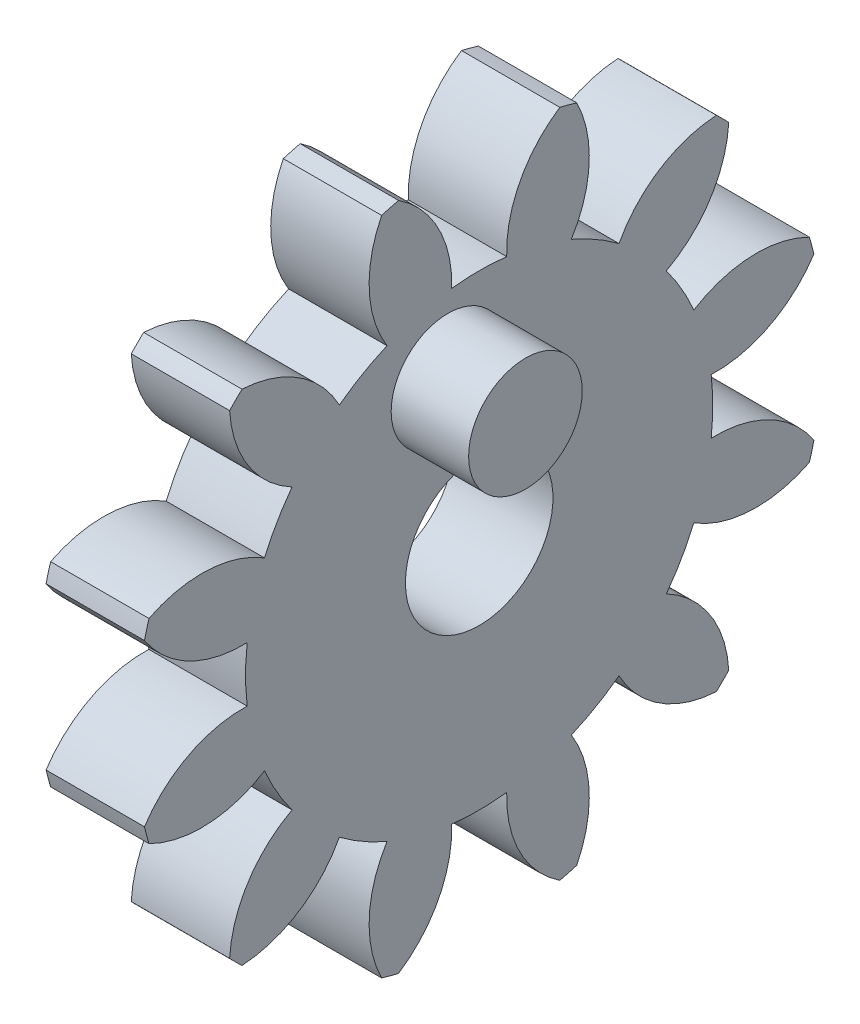
SolidWorks part; units mm, degrees
ref_plane "Plane1" through (0, 0, 0) normal (0, 0, 1) x (1, 0, 0)
ref_plane "Plane2" through (0, 0, 0) normal (0, 1, 0) x (1, 0, 0)
ref_plane "Plane3" through (0, 0, 0) normal (1, 0, 0) x (0, 0, -1)
other "Configuration Table"
sketch "HoldingSke" plane through (0, 0, 0) normal (0, 1, 0) x (1, 0, 0)
  line L0 (0, 0) -> (0.1551, -0.0273)
  line L1 (-15, 0) -> (100, 0) construction
  line L2 (0, 0) -> (-2.1039, 2.3779)
  line L3 (0, 0) -> (-11.863, 4.5341)
  line L4 (0, 0) -> (8.5048, 1.4996)
  line L5 (0, 0) -> (-46.8476, -17.4728)
  line L6 (0, 0) -> (-10.5278, -7.1032)
  line L7 (-2.1039, 2.3779) -> (3.3635, 27.1825)
  line L8 (-76.2, 54.61) -> (-76.1, 54.61)
  line L9 (-71.009, 38.7566) -> (-53.1078, 45.2721)
  line L10 (-76.2, 71.12) -> (104.1128, 71.12)
  line L11 (0, 0) -> (-12, 0)
  line L12 (-76.2, 101.6) -> (-76.192, 101.6)
  line L13 (24.9733, 27.94) -> (52.9518, 28.4284)
  line L14 (24.9733, 27.94) -> (24.9743, 27.94)
  line L15 (24.9733, 27.94) -> (100.4006, 29.5858)
  line L16 (-63.627, -0.25) -> (-12.827, -0.25)
  circle A0 centre (0, 0) radius 0.4
  circle A1 centre (0, 0) radius 12.7
  circle A2 centre (0, 0) radius 37.5
  circle A3 centre (0, 0) radius 9.525
  dimension "MHD" = 25.4
  dimension "Hub_dia" = 75
  dimension "Bore" = 0.8
  dimension "MBD" = 19.05
  dimension "Num_teeth" = 10
  dimension "Pitch" = 0.1575
  dimension "Overall_len" = 50
  dimension "Show_teeth" = 10
  dimension "Thickness" = 12.7
  dimension "OAL" = 25.4001
  dimension "T_dim" = 0.1
  dimension "Ap" = 20
  dimension "H" = 19.05
  dimension "Pitch_radius" = 180.3128
  dimension "Width" = 12
  dimension "Backlash" = 0.008
  dimension "Addendum_fac" = 1
  dimension "Dedendum_fac" = 1.25
  dimension "Clearance_fac" = 0.25
  dimension "Dedendum_add" = 0.001
  dimension "Module" = 0.25
sketch "BasProSke" plane through (0, 0, 0) normal (0, 1, 0) x (1, 0, 0)
  line L0 (-10, 0) -> (60, 0) construction
  line L1 (0, 0) -> (0, 44.45)
  line L2 (0, 0) -> (12.7, 0)
  line L3 (12.7, 0) -> (12.7, 44.45)
  line L4 (12.7, 44.45) -> (0, 44.45)
  dimension "Thickness" = 12.7
  dimension "Diameter" = 88.9
revolve "Base-Revolve" add sketch "BasProSke" angle 360 about L0
sketch "TooCutSke" plane through (0, 0, 0) normal (1, 0, 0) x (0, 0, -1)
  line L1 (0, 0) -> (0, 107) construction
  line L2 (0, 0) -> (-5.3725, 37.7193) construction
  line L3 (0, 0) -> (-19.5794, 73.0714) construction
  line L4 (-5.3725, 37.7193) -> (-9.7897, 36.5357) construction
  arc A0 (3.5522, 29.9513) -> (-3.5522, 29.9513) centre (0, 0) ccw
  arc A1 (10.4397, 43.2328) -> (-10.4397, 43.2328) centre (0, 0) ccw
  circle A2 centre (0, 0) radius 38.1 construction
  circle A3 centre (0, 0) radius 35.8023 construction
  arc A4 (-3.5522, 29.9513) -> (-10.4397, 43.2328) centre (-18.7831, 30.4795) ccw
  arc A5 (10.4397, 43.2328) -> (3.5522, 29.9513) centre (18.7831, 30.4795) ccw
  dimension "Root_dia" = 60.3225
  dimension "Overcut_dia" = 88.9508
  dimension "Pitch_dia" = 76.2
  dimension "Base_dia" = 71.6046
  dimension "Flank_rad" = 15.24
  dimension "Half_ang" = 15
  dimension "Half_CT" = 4.573
extrude "ToothCut" cut sketch "TooCutSke" along normal through all
fillet "Breaks" [suppressed] radius 0.127
fillet "RootFillets" [suppressed] radius 1.5888
pattern_circular "TeethCuts" count 12 every 30 about axis through (-10, 0, 0) along (1, 0, 0) of "ToothCut", "RootFillets", "Breaks"
sketch "HubNeaOneSke" plane through (0, 0, 0) normal (-1, 0, 0) x (0, 0, 1)
  circle A0 centre (0, 0) radius 12.7
  dimension "Diameter" = 25.4
extrude "HubNearOne" [suppressed] add sketch "HubNeaOneSke" along normal blind 12.7001
sketch "HubNeaBotSke" plane through (0, 0, 0) normal (-1, 0, 0) x (0, 0, 1)
  circle A0 centre (0, 0) radius 12.7
  dimension "Diameter" = 25.4
extrude "HubNearBoth" [suppressed] add sketch "HubNeaBotSke" along normal blind 6.35
ref_plane "FarPln" through (12.7, 0, 0) normal (1, 0, 0) x (0, 0, -1)
sketch "HubFarSke" plane through (12.7, 0, 0) normal (1, 0, 0) x (0, 0, -1)
  circle A0 centre (0, 0) radius 12.7
  dimension "Diameter" = 25.4
extrude "HubFar" [suppressed] add sketch "HubFarSke" along normal blind 6.35
sketch "BorSke" plane through (0, 0, 0) normal (1, 0, 0) x (0, 0, -1)
  circle A0 centre (0, 0) radius 9.525
  dimension "Diameter" = 19.05
extrude "Bore" cut sketch "BorSke" along normal mid plane 50.8001
sketch "KeySke" plane through (0, 0, 0) normal (1, 0, 0) x (0, 0, -1)
  line L0 (-0.05, 0) -> (-0.05, 12.065)
  line L1 (-0.05, 12.065) -> (0.05, 12.065)
  line L2 (0.05, 12.065) -> (0.05, 0)
  line L3 (0, 0) -> (0, 34) construction
  line L4 (-0.05, 0) -> (0.05, 0)
  dimension "Offset" = 12.065
  dimension "Width" = 0.1
extrude "Keyway" [suppressed] cut sketch "KeySke" along normal mid plane 50.8001
pattern_circular "Keyway2" [suppressed] count 2 every 90 about axis through (-10, 0, 0) along (1, 0, 0)
sketch "Sketch1" plane through (12.7, 0, 0) normal (1, 0, 0) x (0, 0, -1)
  circle A0 centre (-4.0293, 20.066) radius 7.3334
extrude "Boss-Extrude1" add sketch "Sketch1" along normal blind 10
equation "' \"Module@HoldingSke\" = 6.35"
equation "' \"Num_teeth@HoldingSke\" = 12"
equation "' \"Ap@HoldingSke\" =  20"
equation "' \"Ap@HoldingSke\" = 20"
equation "' \"Width@HoldingSke\" = 0.5 * 25.4"
equation "' \"Hub_dia@HoldingSke\"= 1 * 25.4"
equation "' \"Hub_dia@HoldingSke\" = 1 * 25.4"
equation "' \"Overall_len@HoldingSke\" = 1.0 * 25.4"
equation "' \"Bore@HoldingSke\" = 0.75 * 25.4"
equation "' \"T_dim@HoldingSke\" = 0.1 * 25.4"
equation "' \"Width@KeySke\" = 0.25 * 25.4"
equation "' \"Show_teeth@HoldingSke\" = 13"
equation "' \"Backlash@HoldingSke\" = 0.009 * 25.4"
equation "' \"Addendum_fac@HoldingSke\" = 1.0"
equation "' \"Dedendum_fac@HoldingSke\" = 1.25"
equation "' \"Dedendum_add@HoldingSke\" = 0.00005 * 25.4"
equation "' \"Clearance_fac@HoldingSke\" = 0.25"
equation "\"Pitch@HoldingSke\" = 1 / \"Module@HoldingSke\""
equation "\"Overcut_dia@TooCutSke\" = (\"Num_teeth@HoldingSke\" + 2 * \"Addendum_fac@HoldingSke\") / \"Pitch@HoldingSke\" + 0.002 * 25.4"
equation "\"Pitch_dia@TooCutSke\" = \"Num_teeth@HoldingSke\" / \"Pitch@HoldingSke\""
equation "\"Base_dia@TooCutSke\" = \"Num_teeth@HoldingSke\" / \"Pitch@HoldingSke\" * cos((\"Ap@HoldingSke\"  * 3.14159265 / 180))"
equation "\"Root_dia@TooCutSke\" = (\"Num_teeth@HoldingSke\" + 2) / \"Pitch@HoldingSke\" - 2 * (\"Addendum_fac@HoldingSke\" + \"Dedendum_fac@HoldingSke\") / \"Pitch@HoldingSke\" - \"Dedendum_add@HoldingSke\" * 2"
equation "\"Half_ang@TooCutSke\" = 180 / \"Num_teeth@HoldingSke\""
equation "\"Half_CT@TooCutSke\" = \"Num_teeth@HoldingSke\" / \"Pitch@HoldingSke\" * sin((3.14159265 / 2 / \"Num_teeth@HoldingSke\")) / 2 - 7 * \"Backlash@HoldingSke\" / 4"
equation "\"Flank_rad@TooCutSke\" = \"Num_teeth@HoldingSke\" / \"Pitch@HoldingSke\" / 5"
equation "\"Radius@RootFillets\" = \"Clearance_fac@HoldingSke\" / \"Pitch@HoldingSke\" + \"Dedendum_add@HoldingSke\""
equation "\"Break_rad@Breaks\" = 0.02 / \"Pitch@HoldingSke\""
equation "\"Thickness@HoldingSke\" = \"Width@HoldingSke\""
equation "\"OAL@HoldingSke\" = \"Thickness@HoldingSke\""
equation "\"MHD@HoldingSke\" = (\"Num_teeth@HoldingSke\" + 2) / \"Pitch@HoldingSke\" - 2 * (\"Addendum_fac@HoldingSke\" + \"Dedendum_fac@HoldingSke\")  / \"Pitch@HoldingSke\" - \"Dedendum_add@HoldingSke\" * 2"
equation "\"MBD@HoldingSke\" = (\"Num_teeth@HoldingSke\" + 2) / \"Pitch@HoldingSke\" - 2 * (\"Addendum_fac@HoldingSke\" + \"Dedendum_fac@HoldingSke\")  / \"Pitch@HoldingSke\" - \"Dedendum_add@HoldingSke\" * 2 - 0.002 * 25.4"
equation "\"MHD@HoldingSke\" = ((sgn( \"MHD@HoldingSke\" - \"Hub_dia@HoldingSke\" )-1)*( \"MHD@HoldingSke\" - \"Hub_dia@HoldingSke\" ))/-2+ \"Hub_dia@HoldingSke\""
equation "\"MBD@HoldingSke\" = ((sgn( \"MBD@HoldingSke\" - \"Bore@HoldingSke\" )-1)*( \"MBD@HoldingSke\" - \"Bore@HoldingSke\" ))/-2+ \"Bore@HoldingSke\""
equation "\"OAL@HoldingSke\" = ((sgn( \"OAL@HoldingSke\" - \"Overall_len@HoldingSke\" )+1)*( \"OAL@HoldingSke\" - \"Overall_len@HoldingSke\" ))/2 + \"Overall_len@HoldingSke\" + 0.000002 * 25.4"
equation "\"Num_teeth@TeethCuts\" = int( \"Show_teeth@HoldingSke\" ) + 1"
equation "\"Num_teeth@TeethCuts\" = ((sgn( \"Num_teeth@TeethCuts\" - \"Num_teeth@HoldingSke\" )-1)*( \"Num_teeth@TeethCuts\" - \"Num_teeth@HoldingSke\" ))/-2+ \"Num_teeth@HoldingSke\""
equation "\"Num_teeth@TeethCuts\" = ((sgn( \"Num_teeth@TeethCuts\" - 2.0)+1)*( \"Num_teeth@TeethCuts\" - 2.0))/2 +2.0"
equation "\"Angle@TeethCuts\" = 360.0 / \"Num_teeth@HoldingSke\""
equation "\"Diameter@BasProSke\" = (\"Num_teeth@HoldingSke\" + 2 * \"Addendum_fac@HoldingSke\") / \"Pitch@HoldingSke\""
equation "\"Thickness@BasProSke\"  = \"Thickness@HoldingSke\""
equation "' \"Fillet_rad@BasProSke\" =  \"Thickness@HoldingSke\" * 0.05"
equation "' \"Fillet_rad@BasProSke\" = \"Thickness@HoldingSke\" * 0.05"
equation "\"MHD@HoldingSke\" = ((sgn( \"MHD@HoldingSke\" - \"Root_dia@TooCutSke\" )-1)*( \"MHD@HoldingSke\" - \"Root_dia@TooCutSke\" ))/-2+ \"Root_dia@TooCutSke\""
equation "\"Diameter@HubNeaOneSke\" = \"MHD@HoldingSke\""
equation "\"Length@HubNearOne\" = \"OAL@HoldingSke\" - \"Thickness@BasProSke\""
equation "\"Diameter@HubNeaBotSke\" = \"MHD@HoldingSke\""
equation "\"Length@HubNearBoth\" = ( \"OAL@HoldingSke\" - \"Thickness@BasProSke\" ) / 2.0"
equation "\"Thickness@FarPln\" = \"Thickness@BasProSke\""
equation "\"Diameter@HubFarSke\" = \"MHD@HoldingSke\""
equation "\"Length@HubFar\" = ( \"OAL@HoldingSke\" - \"Thickness@BasProSke\" ) / 2.0"
equation "\"Diameter@BorSke\" = \"MBD@HoldingSke\""
equation "\"D1@Bore\" = \"OAL@HoldingSke\" * 2.0"
equation "\"D1@Keyway\" = \"OAL@HoldingSke\" * 2.0"
equation "\"Offset@KeySke\" = \"T_dim@HoldingSke\" + \"MBD@HoldingSke\" / 2.0"
